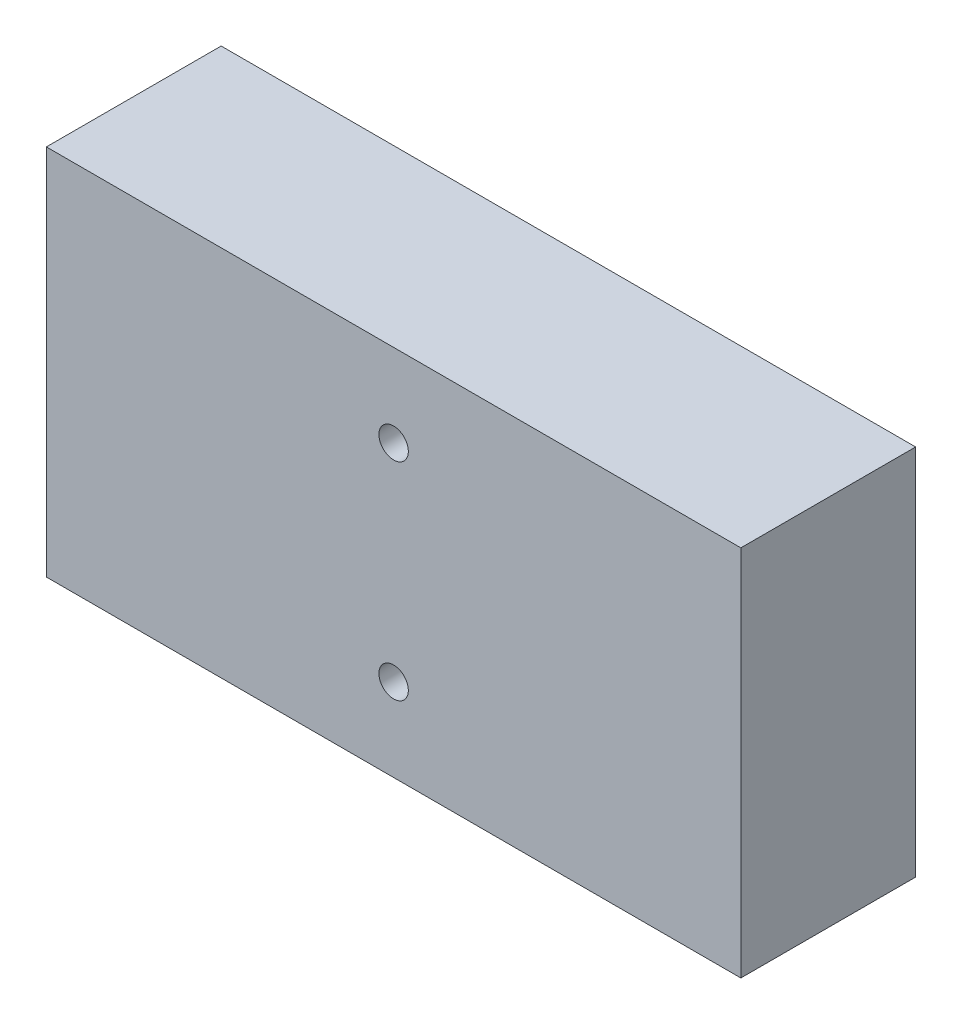
SolidWorks part; units mm, degrees
ref_plane "Front Plane" through (0, 0, 0) normal (0, 0, 1) x (1, 0, 0)
ref_plane "Top Plane" through (0, 0, 0) normal (0, 1, 0) x (1, 0, 0)
ref_plane "Right Plane" through (0, 0, 0) normal (1, 0, 0) x (0, 0, -1)
sketch "Sketch1" plane through (0, 0, 0) normal (0, 0, 1) x (1, 0, 0)
  line L0 (0, 0) -> (10.4425, 0) construction
  line L1 (-37.75, -20.25) -> (37.75, -20.25)
  line L2 (-37.75, -20.25) -> (-37.75, 20.25)
  line L3 (-37.75, 20.25) -> (37.75, 20.25)
  line L4 (37.75, -20.25) -> (37.75, 20.25)
  line L5 (-37.75, -20.25) -> (37.75, 20.25) construction
  line L6 (-37.75, 20.25) -> (37.75, -20.25) construction
  circle A0 centre (0, 11.25) radius 1.6
  circle A1 centre (0, -11.25) radius 1.6
  point P0 (0, 0)
  dimension "D3" = 3.2
  dimension "D1" = 40.5
  dimension "D2" = 75.5
  dimension "D4" = 9
  dimension "D5" = 0
extrude "Boss-Extrude1" add sketch "Sketch1" along normal blind 19
